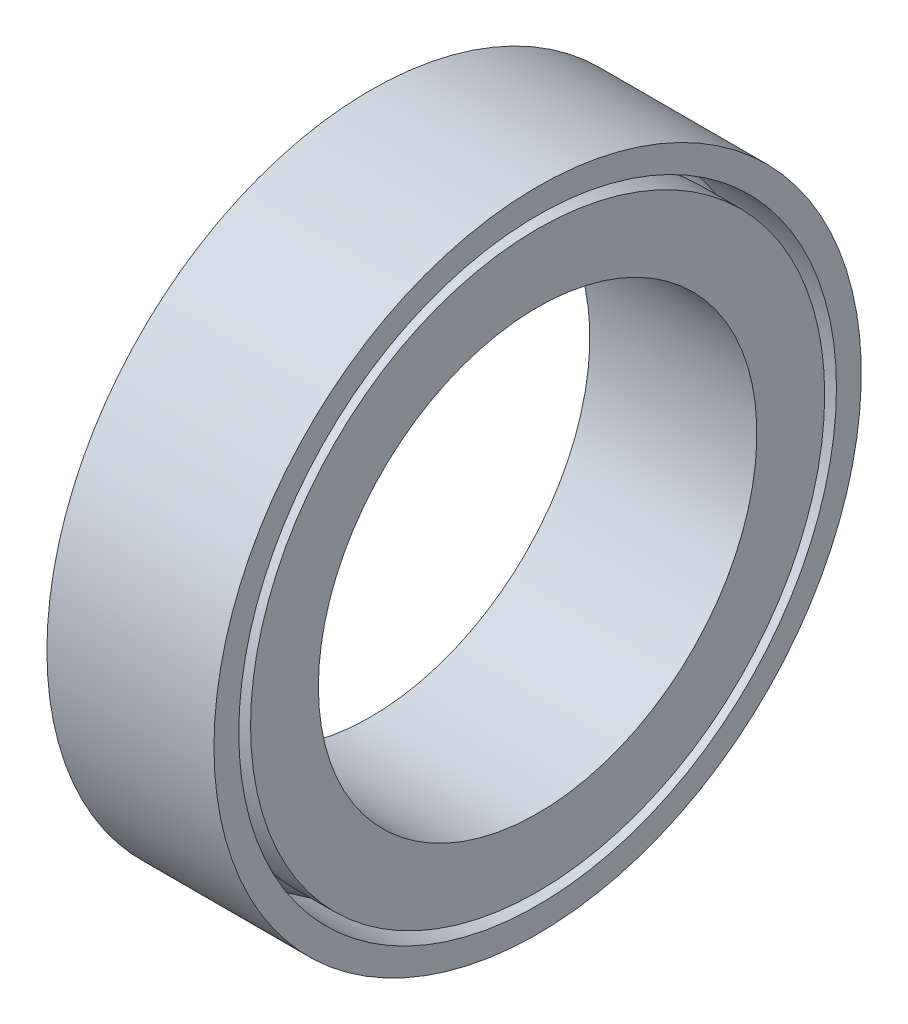
SolidWorks part; units mm, degrees
ref_plane "前视基准面" through (0, 0, 0) normal (0, 0, 1) x (1, 0, 0)
ref_plane "上视基准面" through (0, 0, 0) normal (0, 1, 0) x (1, 0, 0)
ref_plane "右视基准面" through (0, 0, 0) normal (1, 0, 0) x (0, 0, -1)
sketch "草图1" plane through (0, 0, 0) normal (0, 0, 1) x (1, 0, 0)
  line L0 (0, 0) -> (70.9589, 0) construction
  line L1 (0, 10.5) -> (0, 15.5)
  line L2 (0, 15.5) -> (8, 15.5)
  line L3 (8, 15.5) -> (8, 14.3121)
  line L4 (8, 14.3121) -> (3.9905, 14.3121)
  line L5 (2.7897, 12.056) -> (5.9823, 12.056)
  line L7 (3.9905, 14.3121) -> (2.7897, 14.3121)
  line L8 (5.9823, 13.7476) -> (8, 13.7476)
  line L9 (8, 13.7476) -> (8, 10.5)
  line L10 (8, 10.5) -> (0, 10.5)
  line L13 (5.9823, 13.7476) -> (5.9823, 12.056)
  line L14 (2.7897, 14.3121) -> (2.7897, 12.056)
  circle A0 centre (4.4093, 13.0813) radius 1.0411
  dimension "D1" = 21
  dimension "D3" = 31
  dimension "D4" = 8
  dimension "D5" = 8
revolve "旋转2" add sketch "草图1" angle 360 about L0
